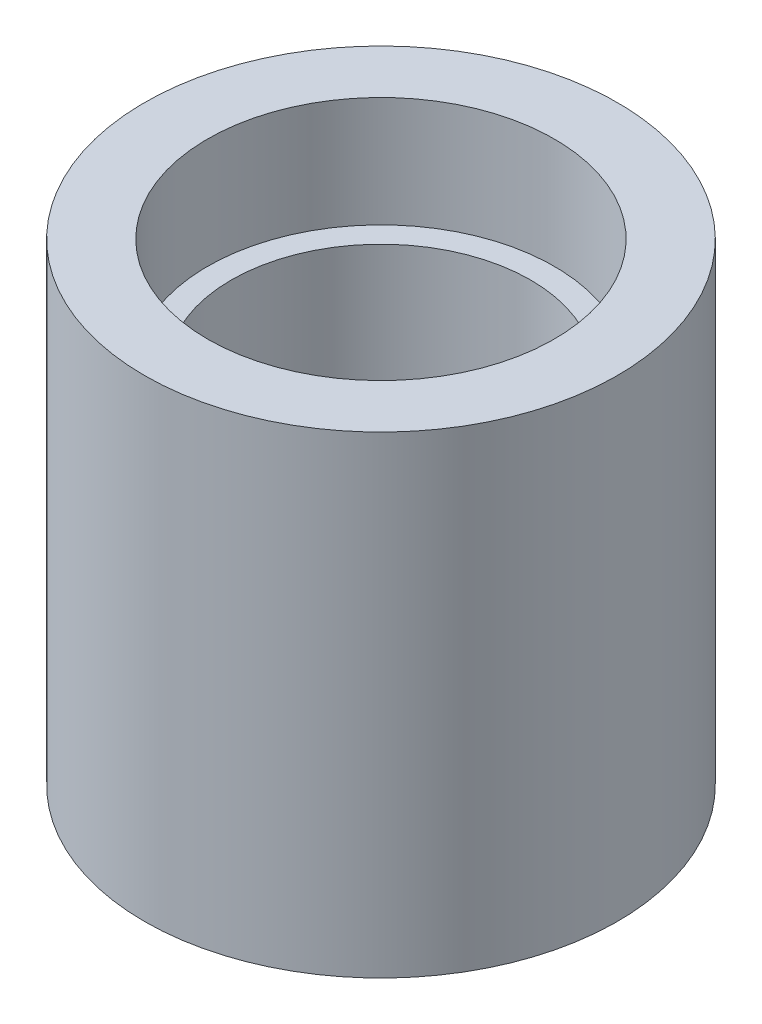
SolidWorks part; units mm, degrees
ref_plane "Alzado" through (0, 0, 0) normal (0, 0, 1) x (1, 0, 0)
ref_plane "Planta" through (0, 0, 0) normal (0, 1, 0) x (1, 0, 0)
ref_plane "Vista lateral" through (0, 0, 0) normal (1, 0, 0) x (0, 0, -1)
sketch "Croquis2" plane through (0, 0, 0) normal (0, 1, 0) x (1, 0, 0)
  circle A0 centre (0, 0) radius 15
  dimension "D1" = 30
extrude "Saliente-Extruir2" add sketch "Croquis2" along normal blind 30
sketch "Croquis3" plane through (0, 30, 0) normal (0, 1, 0) x (1, 0, 0)
  circle A0 centre (0, 0) radius 11
  dimension "D1" = 22
extrude "Cortar-Extruir1" cut sketch "Croquis3" against normal blind 7
sketch "Croquis4" plane through (0, 0, 0) normal (0, -1, 0) x (-1, 0, 0)
  circle A0 centre (0, 0) radius 11
extrude "Cortar-Extruir2" cut sketch "Croquis4" against normal blind 7
sketch "Croquis5" plane through (0, 23, 0) normal (0, 1, 0) x (1, 0, 0)
  circle A0 centre (0, 0) radius 9.5
extrude "Cortar-Extruir3" cut sketch "Croquis5" against normal up to next
